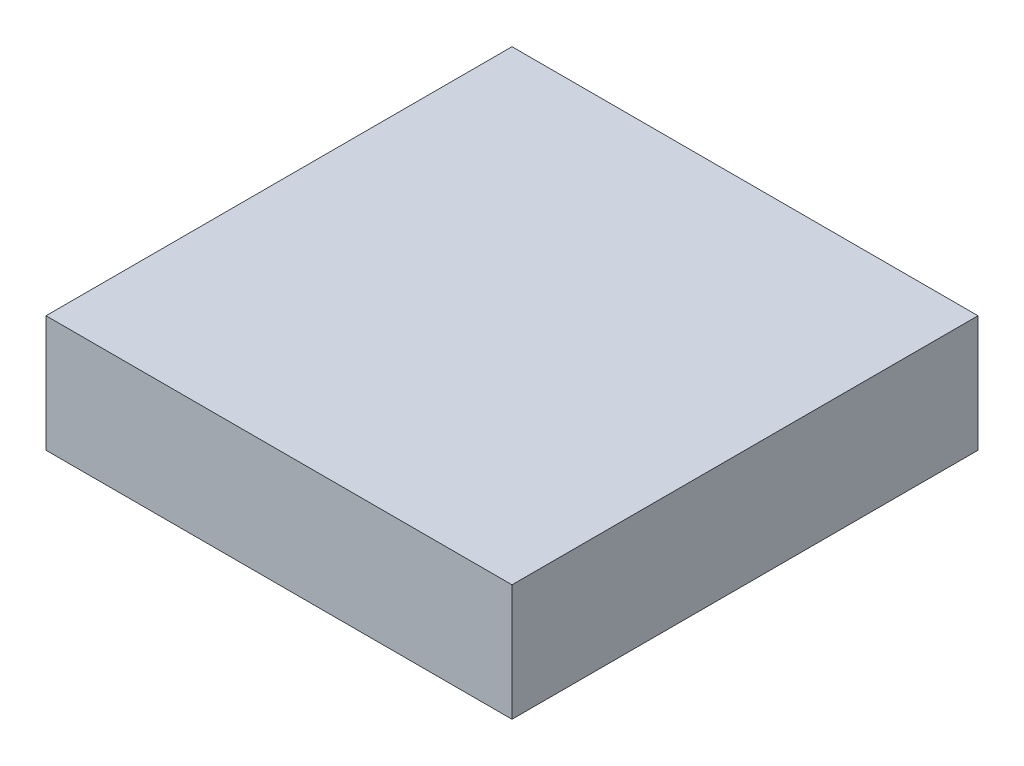
SolidWorks part; units mm, degrees
ref_plane "Alzado" through (0, 0, 0) normal (0, 0, 1) x (1, 0, 0)
ref_plane "Planta" through (0, 0, 0) normal (0, 1, 0) x (1, 0, 0)
ref_plane "Vista lateral" through (0, 0, 0) normal (1, 0, 0) x (0, 0, -1)
sketch "Croquis1" plane through (0, 0, 0) normal (0, 1, 0) x (1, 0, 0)
  line L1 (0, 0) -> (40, 0)
  line L2 (0, 0) -> (0, 40)
  line L3 (0, 40) -> (40, 40)
  line L4 (40, 0) -> (40, 40)
  dimension "D1" = 40
  dimension "D2" = 40
extrude "Saliente-Extruir1" add sketch "Croquis1" along normal blind 10
